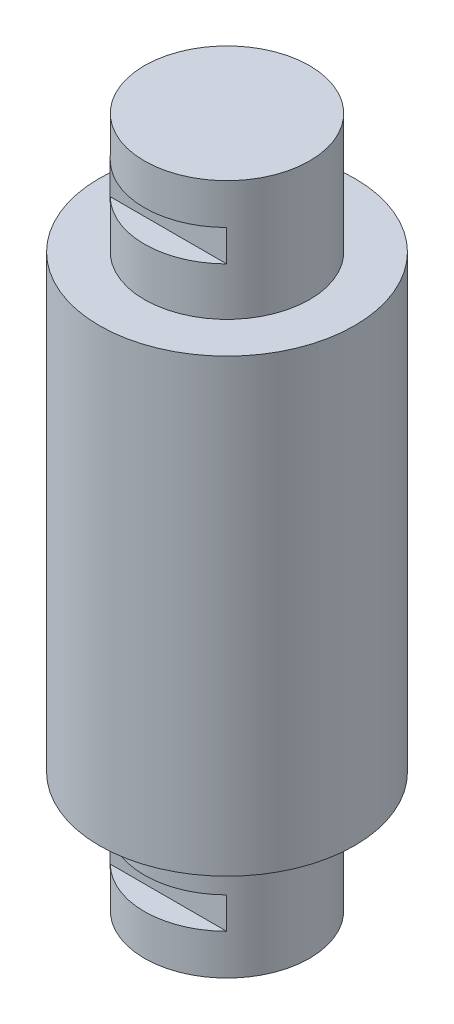
SolidWorks part; units mm, degrees
ref_plane "Front Plane" through (0, 0, 0) normal (1, 0, 0) x (0, 1, 0)
ref_plane "Top Plane" through (0, 0, 0) normal (0, 0, 1) x (0, 1, 0)
ref_plane "Right Plane" through (0, 0, 0) normal (0, 1, 0) x (-1, 0, 0)
sketch "Sketch1" plane through (0, 0, 0) normal (0, 1, 0) x (-1, 0, 0)
  circle A0 centre (0, 0) radius 42.5
  dimension "D1" = 85
extrude "Boss-Extrude1" add sketch "Sketch1" along normal mid plane 150
sketch "Sketch2" plane through (0, 75, 0) normal (0, 1, 0) x (-1, 0, 0)
  circle A0 centre (0, 0) radius 27.5
  dimension "D1" = 55
extrude "Boss-Extrude2" add sketch "Sketch2" along normal blind 40
sketch "Sketch3" plane through (0, 0, 0) normal (1, 0, 0) x (0, 1, 0)
  line L0 (91, 27.5) -> (91, 19.5)
  line L1 (115, 27.5) -> (75, 27.5) construction
  line L2 (91, 19.5) -> (101.5, 19.5)
  line L3 (101.5, 19.5) -> (101.5, 27.5)
  line L4 (101.5, 27.5) -> (101.5, 29.5)
  line L5 (101.5, 29.5) -> (91, 29.5)
  line L6 (91, 29.5) -> (91, 27.5)
  line L7 (115, -27.5) -> (115, 27.5) construction
  line L8 (0, 0) -> (147.014, 0) construction
  dimension "D1" = 8
  dimension "D2" = 10.5
  dimension "D3" = 13.5
  dimension "D4" = 2
extrude "Cut-Extrude1" cut sketch "Sketch3" against normal through all both and the other way through all
mirror "Mirror1" about plane through (0, 0, 0) normal (0, 1, 0) of "Boss-Extrude2", "Cut-Extrude1"
